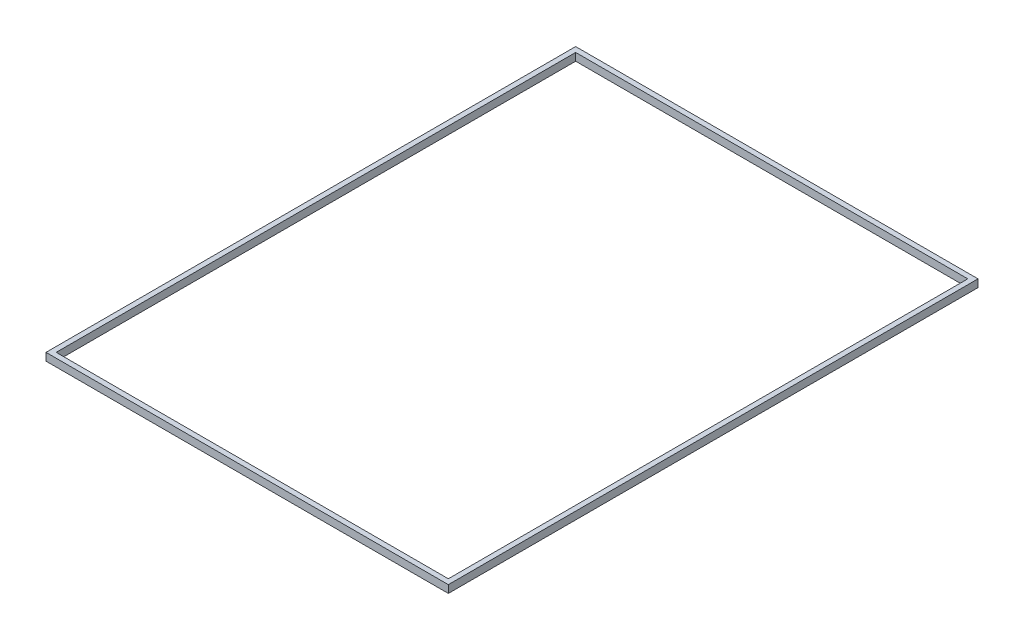
SolidWorks part; units mm, degrees
ref_plane "Front Plane" through (0, 0, 0) normal (0, 0, 1) x (1, 0, 0)
ref_plane "Top Plane" through (0, 0, 0) normal (0, 1, 0) x (1, 0, 0)
ref_plane "Right Plane" through (0, 0, 0) normal (1, 0, 0) x (0, 0, -1)
sketch "Sketch1" plane through (0, 0, 0) normal (0, 1, 0) x (1, 0, 0)
  line L0 (-200, 200) -> (-200, -20600)
  line L1 (0, 0) -> (15400, 0)
  line L2 (0, 0) -> (0, -20400)
  line L3 (0, -20400) -> (15400, -20400)
  line L4 (15400, 0) -> (15400, -20400)
  line L5 (0, 0) -> (15400, -20400) construction
  line L6 (0, -20400) -> (15400, 0) construction
  line L7 (-200, -20600) -> (15600, -20600)
  line L8 (15600, 200) -> (15600, -20600)
  line L9 (-200, 200) -> (15600, 200)
  point P4 (7700, -10200)
  dimension "D1" = 20400
  dimension "D2" = 15400
  dimension "D3" = 200
extrude "Boss-Extrude1" add sketch "Sketch1" along normal blind 300
